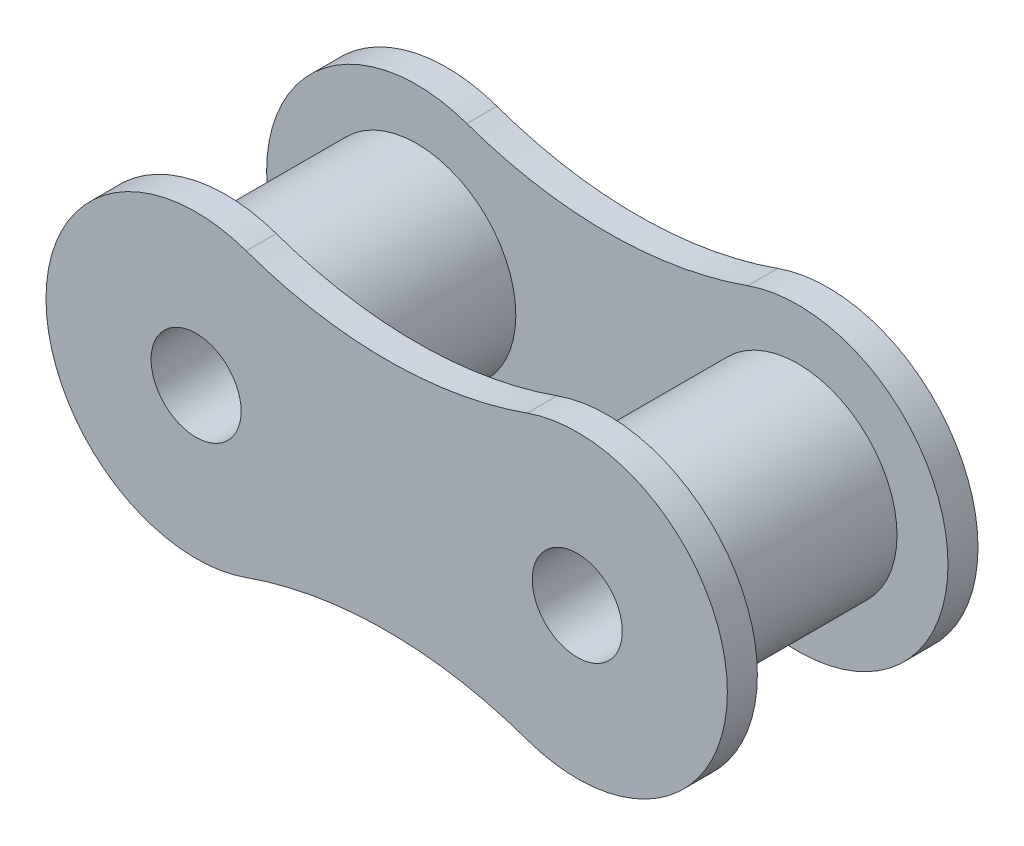
SolidWorks part; units mm, degrees
material "AISI 304"
ref_plane "Plane1" through (0, 0, 0) normal (0, 0, 1) x (1, 0, 0)
ref_plane "Plane2" through (0, 0, 0) normal (0, 1, 0) x (1, 0, 0)
ref_plane "Plane3" through (0, 0, 0) normal (1, 0, 0) x (0, 0, -1)
sketch "Sketch1" plane through (0, 0, 0) normal (0, 0, 1) x (1, 0, 0)
  line L0 (3.175, 2.6926) -> (3.175, -2.6926) construction
  arc A0 (0.8355, 2.3562) -> (0.8355, -2.3562) centre (0, 0) ccw
  circle A4 centre (0, 0) radius 0.75
  arc A8 (5.5145, 2.3562) -> (5.5145, -2.3562) centre (6.35, 0) cw
  circle A9 centre (6.35, 0) radius 0.75
  arc A10 (0.8355, -2.3562) -> (5.5145, -2.3562) centre (3.175, -8.9537) cw
  arc A11 (0.8355, 2.3562) -> (5.5145, 2.3562) centre (3.175, 8.9537) ccw
  dimension "D1" = 5
  dimension "D2" = 3.175
  dimension "D6" = 1.5
  dimension "D3" = 7
extrude "Boss-Extrude1" add sketch "Sketch1" along normal blind 0.5
sketch "Sketch2" plane through (0, 0, 0.5) normal (0, 0, 1) x (1, 0, 0)
  circle A0 centre (0, 0) radius 1.651
  circle A2 centre (6.35, 0) radius 1.651
  circle M2 centre (0, 0) radius 0.75
  circle M7 centre (6.35, 0) radius 0.75
  dimension "D1" = 3.302
  dimension "D2" = 3.302
extrude "Boss-Extrude2" add sketch "Sketch2" along normal blind 3.175 contours A2 M7 | A0 M2
ref_plane "Plane4" through (0, 0, 2.0875) normal (0, 0, 1) x (1, 0, 0)
mirror "Mirror1" about plane through (0, 0, 2.0875) normal (0, 0, 1) of bodies 105 104
